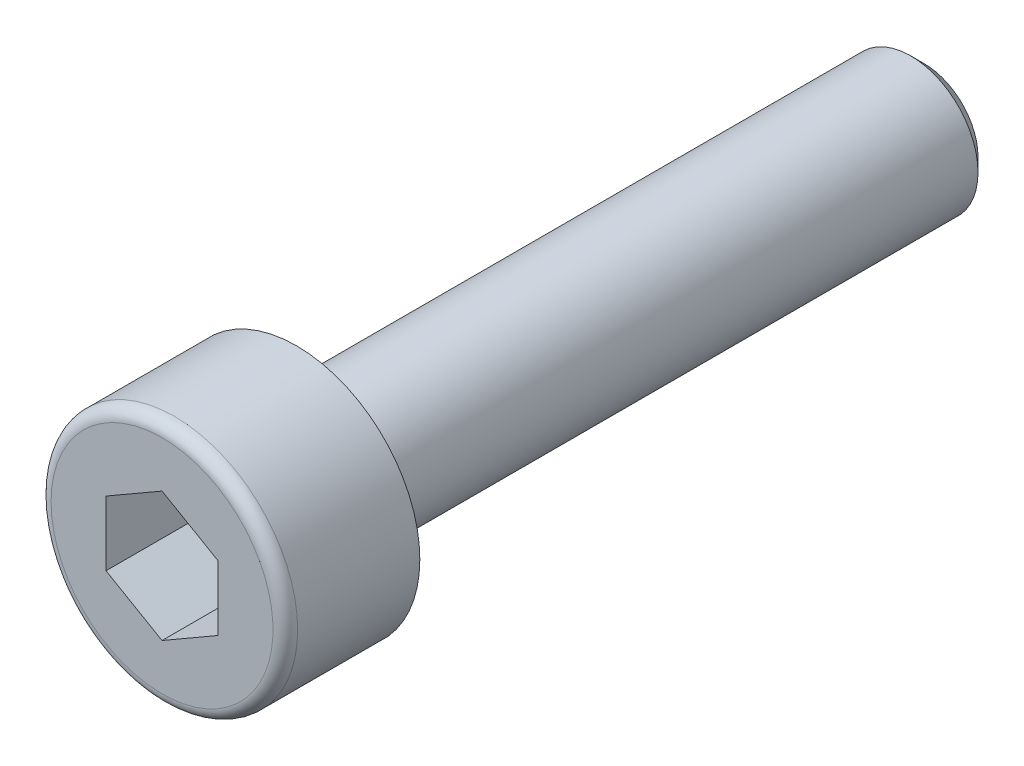
SolidWorks part; units mm, degrees
material "普通碳钢"
ref_plane "前视基准面" through (0, 0, 0) normal (0, 0, 1) x (1, 0, 0)
ref_plane "上视基准面" through (0, 0, 0) normal (0, 1, 0) x (1, 0, 0)
ref_plane "右视基准面" through (0, 0, 0) normal (1, 0, 0) x (0, 0, -1)
sketch "草图1" plane through (0, 0, 0) normal (1, 0, 0) x (0, 0, -1)
  line L0 (-3, 0) -> (30, 0) construction
  line L1 (-3, 0) -> (-3, 2.75)
  line L2 (-3, 2.75) -> (0, 2.75)
  line L3 (0, 2.75) -> (0, 1.5)
  line L4 (0, 1.5) -> (30, 1.5)
  line L5 (30, 1.5) -> (30, 0)
  point P3 (12, 1.5)
  dimension "A" = 5.5
  dimension "E" = 3
  dimension "L" = 30
  dimension "(e)" = 18
  dimension "M" = 3
sketch "草图2" plane through (0, 0, 0) normal (0, 0, 1) x (1, 0, 0)
  line L1 (0, 1.4434) -> (-1.25, 0.7217)
  line L2 (-1.25, 0.7217) -> (-1.25, -0.7217)
  line L3 (-1.25, -0.7217) -> (0, -1.4434)
  line L4 (0, -1.4434) -> (1.25, -0.7217)
  line L5 (1.25, -0.7217) -> (1.25, 0.7217)
  line L6 (1.25, 0.7217) -> (0, 1.4434)
  circle A0 centre (0, 0) radius 1.25 construction
  dimension "B" = 2.5
sketch "草图3" plane through (0, 0, 0) normal (1, 0, 0) x (0, 0, -1)
  line L0 (-3, 0) -> (-3, 2.75) construction
  line L1 (-3, 2.75) -> (0, 2.75) construction
  line L3 (0, 2.75) -> (0, 1.5) construction
  line L6 (-3, 0) -> (-3, 2.75)
  line L7 (-3, 2.75) -> (0, 2.75)
  line L8 (0, 1.5) -> (14, 1.5)
  line L9 (0, 2.75) -> (0, 1.5)
  line L10 (-3, 0) -> (14, 0)
  line L11 (14, 1.5) -> (14, 0)
  dimension "D1" = 14
revolve "旋转1" add sketch "草图3" angle 360 about L10
cosmetic thread "装饰螺纹线1" parameters "D2"=2.459
sketch "草图4" plane through (0, 0, 3) normal (0, 0, 1) x (1, 0, 0)
  line L0 (0, 1.4434) -> (-1.25, 0.7217) construction
  line L1 (-1.25, 0.7217) -> (-1.25, -0.7217) construction
  line L2 (-1.25, -0.7217) -> (0, -1.4434) construction
  line L3 (0, -1.4434) -> (1.25, -0.7217) construction
  line L4 (1.25, -0.7217) -> (1.25, 0.7217) construction
  line L5 (1.25, 0.7217) -> (0, 1.4434) construction
  line L6 (0, 1.4434) -> (-1.25, 0.7217)
  line L7 (-1.25, 0.7217) -> (-1.25, -0.7217)
  line L8 (-1.25, -0.7217) -> (0, -1.4434)
  line L9 (0, -1.4434) -> (1.25, -0.7217)
  line L10 (1.25, -0.7217) -> (1.25, 0.7217)
  line L11 (1.25, 0.7217) -> (0, 1.4434)
extrude "切除-拉伸1" cut sketch "草图4" against normal blind 1.925
fillet "圆角1" radius 0.275 1 edges at (2.75, 0, 3)
chamfer "倒角1" distance 0.3 angle 45 1 edges at (1.5, 0, -14)
